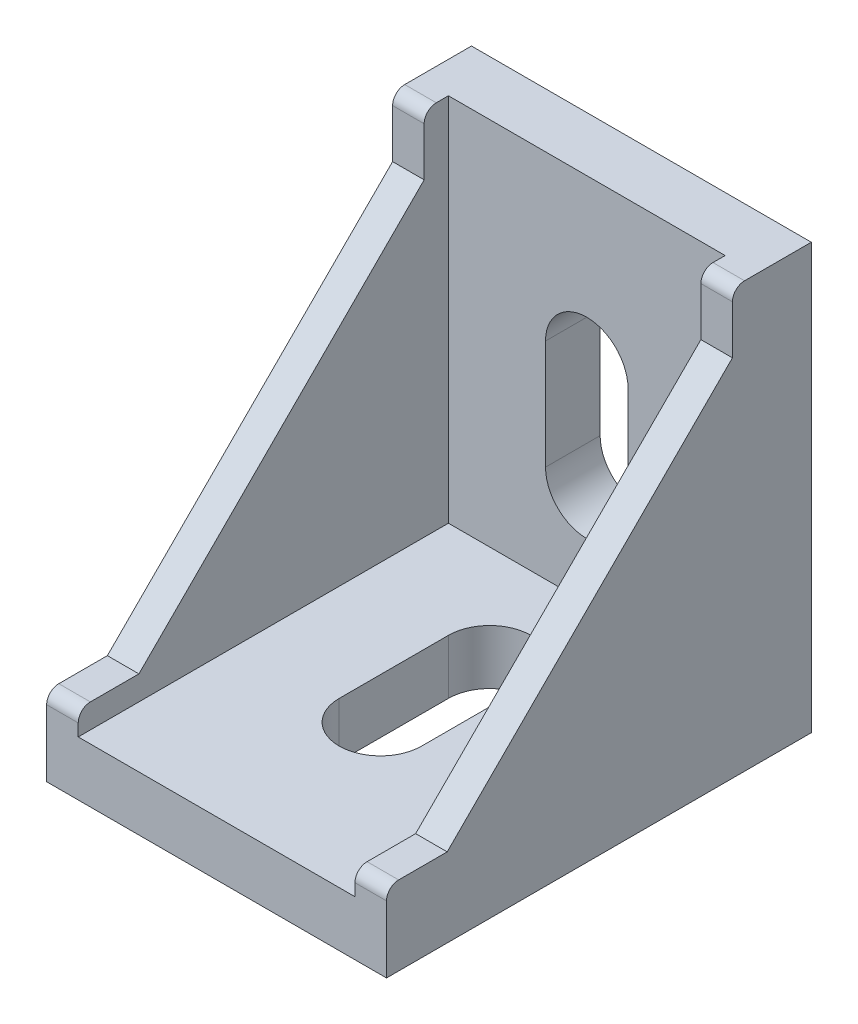
SolidWorks part; units mm, degrees
ref_plane "前视基准面" through (0, 0, 0) normal (0, 0, 1) x (1, 0, 0)
ref_plane "上视基准面" through (0, 0, 0) normal (0, 1, 0) x (1, 0, 0)
ref_plane "右视基准面" through (0, 0, 0) normal (1, 0, 0) x (0, 0, -1)
sketch "草图1" plane through (0, 0, 0) normal (0, 0, 1) x (1, 0, 0)
  line L1 (-14, -17.5) -> (14, -17.5)
  line L2 (-14, -17.5) -> (-14, 17.5)
  line L3 (-14, 17.5) -> (14, 17.5)
  line L4 (14, -17.5) -> (14, 17.5)
  line L5 (-14, -17.5) -> (14, 17.5) construction
  line L6 (-14, 17.5) -> (14, -17.5) construction
  point P0 (0, 0)
  dimension "D1" = 28
  dimension "D2" = 35
extrude "凸台-拉伸1" add sketch "草图1" along normal blind 4.5
sketch "草图2" plane through (0, -17.5, 0) normal (0, -1, 0) x (1, 0, 0)
  line L0 (-14, 0) -> (14, 0)
  line L1 (-14, 0) -> (-14, 35)
  line L2 (14, 0) -> (14, 35)
  line L3 (-14, 35) -> (14, 35)
  dimension "D1" = 35
extrude "凸台-拉伸2" add sketch "草图2" against normal blind 4.5
sketch "草图3" plane through (-14, 0, 0) normal (-1, 0, 0) x (0, 0, 1)
  line L0 (4.5, 17.5) -> (6.5, 17.5)
  line L1 (6.5, 17.5) -> (6.5, 12.5)
  line L2 (6.5, 12.5) -> (30, -11)
  line L3 (30, -11) -> (35, -11)
  line L4 (35, -11) -> (35, -13)
  line L5 (4.5, 17.5) -> (4.5, -13)
  line L6 (4.5, -13) -> (35, -13)
  dimension "D1" = 2
  dimension "D2" = 5
  dimension "D3" = 5
  dimension "D4" = 2
extrude "凸台-拉伸3" add sketch "草图3" against normal blind 2.6
mirror "镜向1" about plane through (0, 0, 0) normal (1, 0, 0) of "凸台-拉伸3"
sketch "草图4" plane through (0, -17.5, 0) normal (0, -1, 0) x (1, 0, 0)
  line L1 (-2.8267, 34.1298) -> (2.8267, 34.1298)
  line L2 (-2.8267, 34.1298) -> (-2.8267, 32.6554)
  line L3 (-2.8267, 32.6554) -> (2.8267, 32.6554)
  line L4 (2.8267, 34.1298) -> (2.8267, 32.6554)
  line L5 (-2.8267, 34.1298) -> (2.8267, 32.6554) construction
  line L6 (-2.8267, 32.6554) -> (2.8267, 34.1298) construction
  point P0 (0, 33.3926)
extrude "凸台-拉伸4" [suppressed] add sketch "草图4" along normal blind 1.5
sketch "草图5" plane through (0, 0, 4.5) normal (0, 0, 1) x (1, 0, 0)
  line L0 (0, -5) -> (0, 4) construction
  line L1 (-3.4, -5) -> (-3.4, 4)
  line L2 (3.4, -5) -> (3.4, 4)
  line L3 (11.4, 17.5) -> (-11.4, 17.5) construction
  arc A0 (-3.4, -5) -> (3.4, -5) centre (0, -5) ccw
  arc A1 (3.4, 4) -> (-3.4, 4) centre (0, 4) ccw
  point P3 (0, -0.5)
  point P8 (0, 17.5)
  dimension "D1" = 3.4
  dimension "D3" = 13.5
  dimension "D2" = 9
extrude "切除-拉伸1" cut sketch "草图5" against normal through all
sketch "草图6" plane through (0, -13, 0) normal (0, 1, 0) x (1, 0, 0)
  line L0 (0, -12.5) -> (0, -21.5) construction
  line L1 (3.4, -12.5) -> (3.4, -21.5)
  line L2 (-3.4, -12.5) -> (-3.4, -21.5)
  line L3 (11.4, -35) -> (-11.4, -35) construction
  arc A0 (3.4, -12.5) -> (-3.4, -12.5) centre (0, -12.5) ccw
  arc A1 (-3.4, -21.5) -> (3.4, -21.5) centre (0, -21.5) ccw
  point P3 (0, -17)
  dimension "D1" = 3.4
  dimension "D3" = 13.5
  dimension "D2" = 9
extrude "切除-拉伸2" cut sketch "草图6" against normal through all
fillet "圆角1" radius 1 4 edges at (-12.7, -11, 35) (12.7, -11, 35) (12.7, 17.5, 6.5) (-12.7, 17.5, 6.5)
